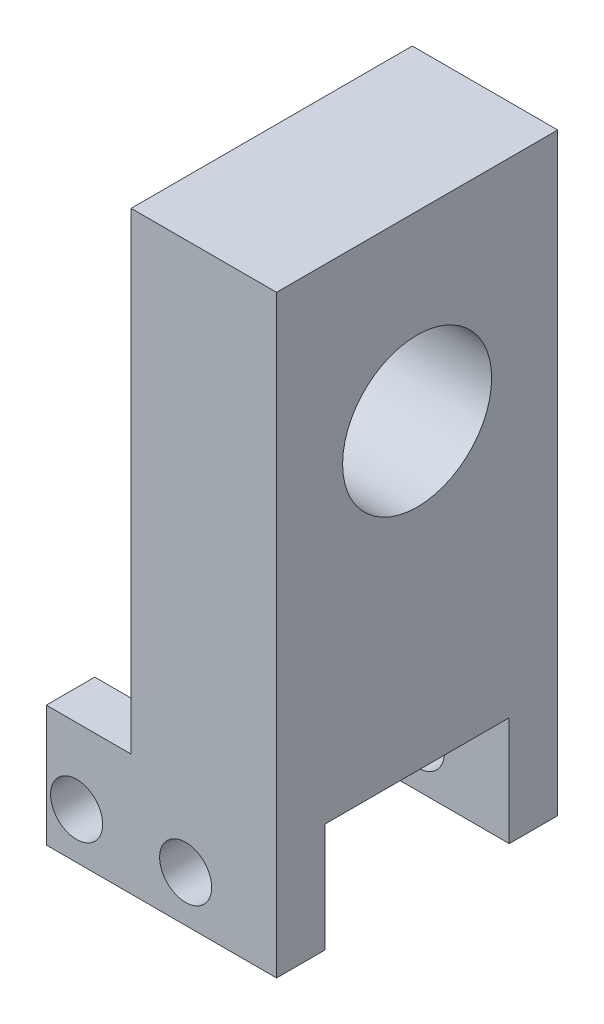
SolidWorks part; units mm, degrees
ref_plane "Front Plane" through (0, 0, 0) normal (0, 0, 1) x (1, 0, 0)
ref_plane "Top Plane" through (0, 0, 0) normal (0, 1, 0) x (1, 0, 0)
ref_plane "Right Plane" through (0, 0, 0) normal (1, 0, 0) x (0, 0, -1)
sketch "Sketch1" plane through (0, 0, 0) normal (0, 0, 1) x (1, 0, 0)
  line L0 (65, 44) -> (77, 44)
  line L1 (77, 44) -> (77, 84)
  line L2 (77, 84) -> (65, 84)
  line L3 (65, 84) -> (65, 44)
extrude "Guided bridge with rod coupling seat" add sketch "Sketch1" along normal blind 23.2 from offset 38.4
sketch "Sketch2" plane through (0, 0, 0) normal (0, 0, 1) x (1, 0, 0)
  line L0 (58, 35) -> (77, 35)
  line L1 (77, 35) -> (77, 45)
  line L2 (77, 45) -> (58, 45)
  line L3 (58, 45) -> (58, 35)
extrude "Lower lap ear clears stop station" add sketch "Sketch2" along normal blind 4 from offset 38.4
sketch "Sketch3" plane through (0, 0, 0) normal (0, 0, 1) x (1, 0, 0)
  line L0 (58, 35) -> (77, 35)
  line L1 (77, 35) -> (77, 45)
  line L2 (77, 45) -> (58, 45)
  line L3 (58, 45) -> (58, 35)
extrude "Upper lap ear clears stop station" add sketch "Sketch3" along normal blind 4 from offset 57.6
sketch "Sketch4" plane through (0, 0, 0) normal (0, 0, 1) x (1, 0, 0)
  circle A0 centre (60.5, 38.8) radius 2.15
  circle A1 centre (69.5, 38.8) radius 2.15
extrude "M4 joint bolt clearance" cut sketch "Sketch4" along normal blind 23.2 from offset 38.4
sketch "Sketch5" plane through (0, 0, 0) normal (1, 0, 0) x (0, 0, -1)
  circle A0 centre (-50, 69) radius 6.15
extrude "Radial floating stud clearance" cut sketch "Sketch5" along normal blind 12 from offset 65
